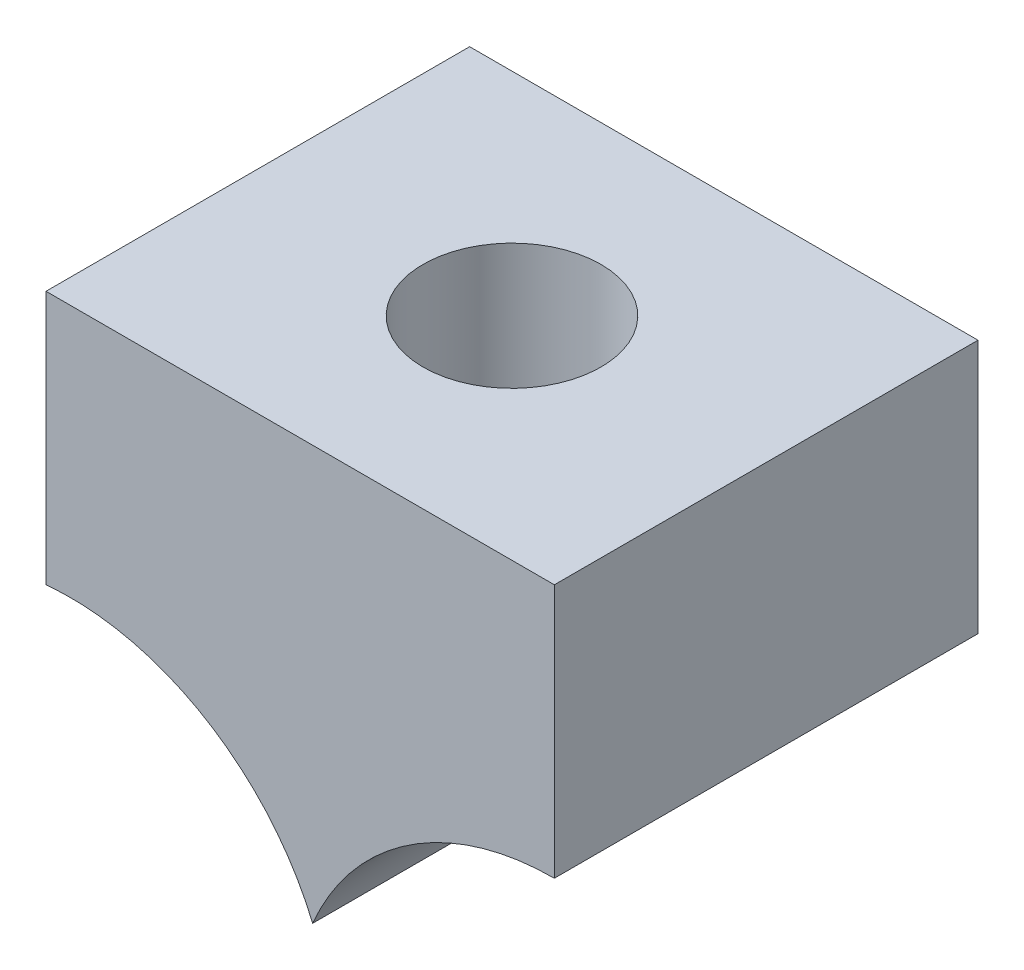
SolidWorks part; units mm, degrees
ref_plane "Front Plane" through (0, 0, 0) normal (0, 0, 1) x (1, 0, 0)
ref_plane "Top Plane" through (0, 0, 0) normal (0, 1, 0) x (1, 0, 0)
ref_plane "Right Plane" through (0, 0, 0) normal (1, 0, 0) x (0, 0, -1)
sketch "Sketch1" plane through (0, 0, 0) normal (0, 0, 1) x (1, 0, 0)
  line L1 (-6, 3) -> (6, 3)
  line L2 (-6, 3) -> (-6, -3)
  line L3 (-6, -3) -> (6, -3) construction
  line L4 (6, 3) -> (6, -3)
  line L5 (-6, 3) -> (6, -3) construction
  line L6 (-6, -3) -> (6, 3) construction
  arc A0 (6, -3) -> (0.2945, -6.7735) centre (6, -9.2) ccw
  arc A1 (-6, -3) -> (0.2945, -6.7735) centre (-5.4223, -9.173) cw
  point P0 (0, 0)
  dimension "D3" = 6.2
  dimension "D4" = 6.2
  dimension "D1" = 12
  dimension "D2" = 6
extrude "Boss-Extrude1" add sketch "Sketch1" along normal blind 10
sketch "Sketch2" plane through (0, 3, 0) normal (0, 1, 0) x (1, 0, 0)
  line L0 (6, 0) -> (-6, 0) construction
  circle A0 centre (0, -5) radius 2.1
  point P4 (0, 0)
  dimension "D1" = 4.2
  dimension "D2" = 5
extrude "Cut-Extrude1" cut sketch "Sketch2" against normal blind 5
sketch "Sketch3" plane through (0, -2, 0) normal (0, 1, 0) x (1, 0, 0)
  circle A0 centre (0, -5) radius 1
  dimension "D1" = 2
extrude "Cut-Extrude2" cut sketch "Sketch3" against normal through all
sketch "Sketch4" plane through (0, 0, 0) normal (0, 1, 0) x (1, 0, 0)
  circle A0 centre (-4.0446, -5) radius 1.0246
  dimension "D1" = 5
extrude "Boss-Extrude2" add sketch "Sketch4" against normal blind 2 draft 45 from offset 2.85
